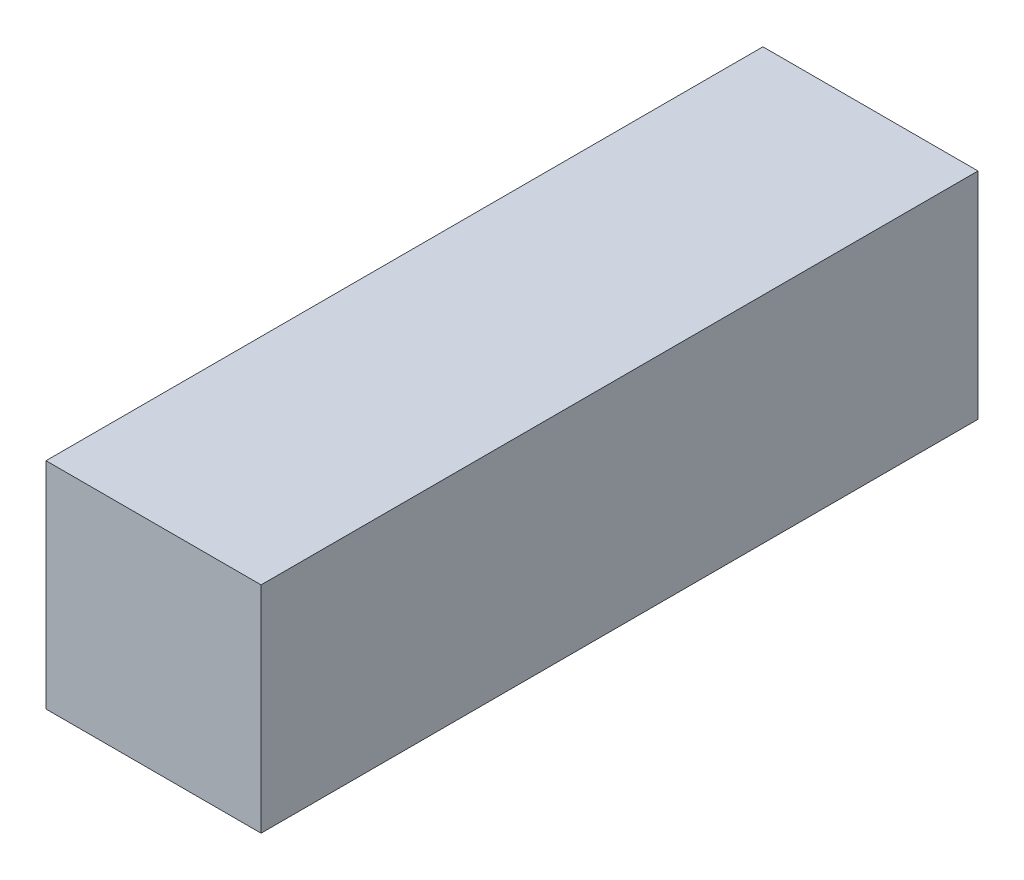
SolidWorks part; units mm, degrees
ref_plane "Front Plane" through (0, 0, 0) normal (0, 0, 1) x (1, 0, 0)
ref_plane "Top Plane" through (0, 0, 0) normal (0, 1, 0) x (1, 0, 0)
ref_plane "Right Plane" through (0, 0, 0) normal (1, 0, 0) x (0, 0, -1)
sketch "Sketch2" plane through (0, 0, 0) normal (0, 0, 1) x (1, 0, 0)
  line L1 (-1.5, -1.5) -> (1.5, -1.5)
  line L2 (-1.5, -1.5) -> (-1.5, 1.5)
  line L3 (-1.5, 1.5) -> (1.5, 1.5)
  line L4 (1.5, -1.5) -> (1.5, 1.5)
  line L5 (-1.5, -1.5) -> (1.5, 1.5) construction
  line L6 (-1.5, 1.5) -> (1.5, -1.5) construction
  point P0 (0, 0)
  dimension "D1" = 3
  dimension "D2" = 3
extrude "Boss-Extrude1" add sketch "Sketch2" along normal blind 10
